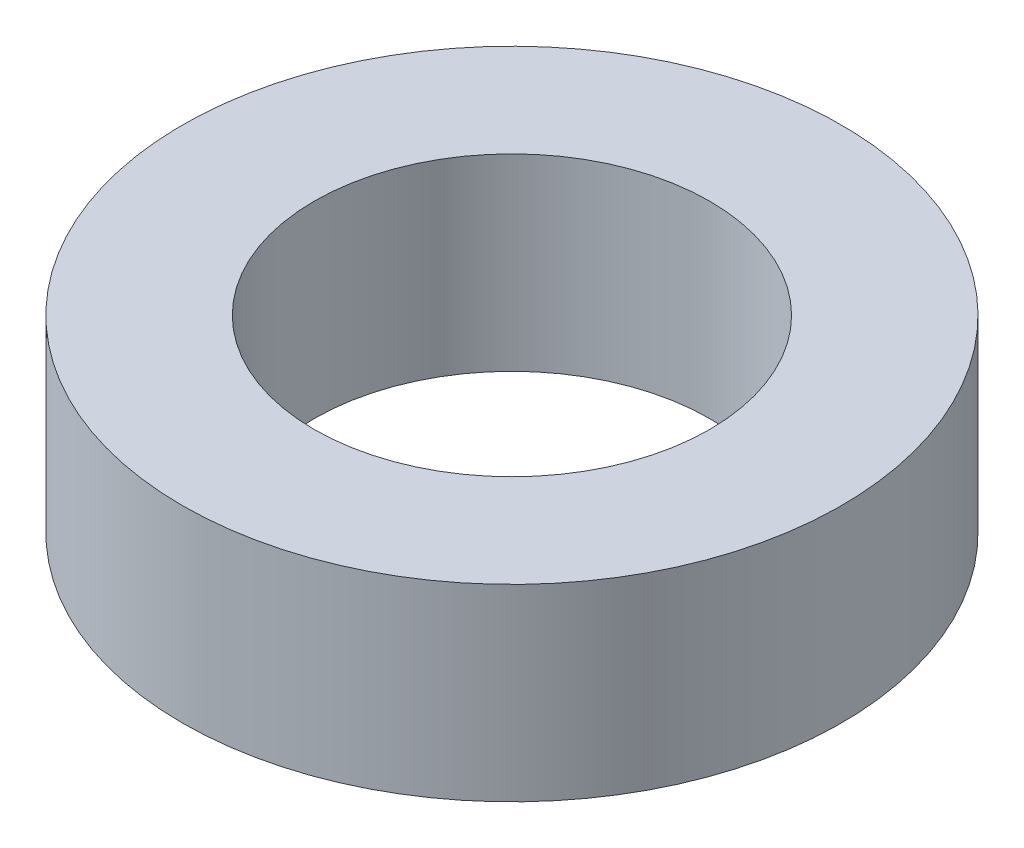
SolidWorks part; units mm, degrees
material "PMMA"
ref_plane "Front Plane" through (0, 0, 0) normal (0, 0, 1) x (1, 0, 0)
ref_plane "Top Plane" through (0, 0, 0) normal (0, 1, 0) x (1, 0, 0)
ref_plane "Right Plane" through (0, 0, 0) normal (1, 0, 0) x (0, 0, -1)
sketch "Sketch1" plane through (0, 0, 0) normal (0, 1, 0) x (1, 0, 0)
  circle A0 centre (0, 0) radius 2.1
  circle A1 centre (0, 0) radius 3.5
  dimension "D1" = 4.2
  dimension "D2" = 7
extrude "Boss-Extrude1" add sketch "Sketch1" along normal blind 2
